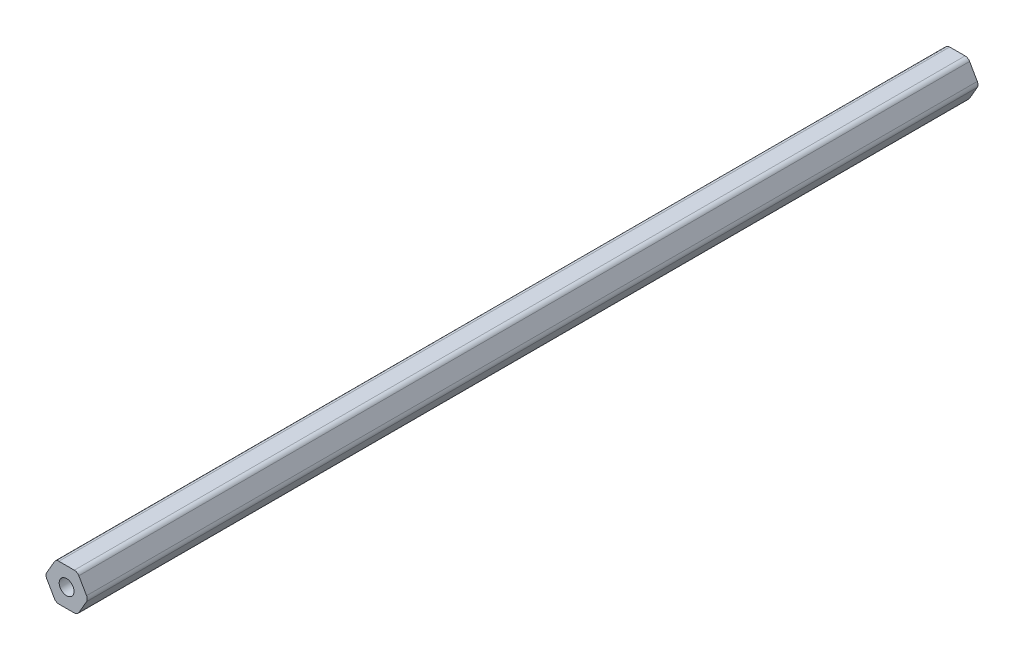
SolidWorks part; units mm, degrees
ref_plane "Front Plane" through (0, 0, 0) normal (0, 0, 1) x (1, 0, 0)
ref_plane "Top Plane" through (0, 0, 0) normal (0, 1, 0) x (1, 0, 0)
ref_plane "Right Plane" through (0, 0, 0) normal (1, 0, 0) x (0, 0, -1)
sketch "Sketch1" plane through (0, 0, 0) normal (0, 0, 1) x (1, 0, 0)
  line L1 (6.7083, 2.6911) -> (3.0421, 9.0411)
  line L2 (3.0421, 9.0411) -> (-4.2902, 9.0411)
  line L3 (-4.2902, 9.0411) -> (-7.9564, 2.6911)
  line L4 (-7.9564, 2.6911) -> (-4.2902, -3.6589)
  line L5 (-4.2902, -3.6589) -> (3.0421, -3.6589)
  line L6 (3.0421, -3.6589) -> (6.7083, 2.6911)
  circle A0 centre (-0.624, 2.6911) radius 6.35 construction
  circle A1 centre (-0.624, 2.6911) radius 2.54
  dimension "D1" = 12.7
extrude "Boss-Extrude1" add sketch "Sketch1" along normal blind 304.8
fillet "Fillet1" radius 1.778 6 edges at (-7.9564, 2.6911, 152.4) (-4.2902, 9.0411, 152.4) (-4.2902, -3.6589, 152.4) (3.0421, -3.6589, 152.4) (6.7083, 2.6911, 152.4) (3.0421, 9.0411, 152.4)
